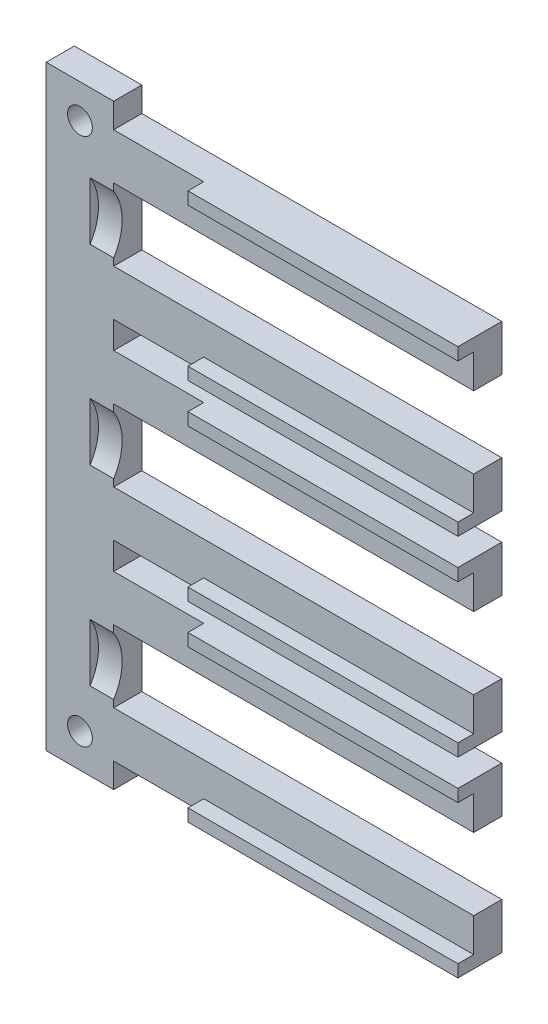
SolidWorks part; units mm, degrees
other "Spring Front Grip Acetal Guide Comb"
other "Spring Front Grip Acetal Guide Comb Left"
ref_plane "Front Plane" through (0, 0, 0) normal (0, 0, 1) x (1, 0, 0)
ref_plane "Top Plane" through (0, 0, 0) normal (0, 1, 0) x (1, 0, 0)
ref_plane "Right Plane" through (0, 0, 0) normal (1, 0, 0) x (0, 0, -1)
sketch3d "Front Grip Acetal Guide Comb sketch datum points"
  point P0 (-66.2917, -55.5, 8.5)
  point P1 (-56.2917, -55.5, 8.5)
  point P2 (-66.2917, -45.5, 8.5)
ref_plane "Front Grip Acetal Guide Comb sketch plane" through (0, 0, 8.5) normal (0, 0, 1) x (1, 0, 0)
sketch "Front Grip Acetal Guide Comb sketch" plane through (0, 0, 8.5) normal (0, 0, 1) x (1, 0, 0)
  line L0 (-66.2917, -55.5) -> (-60.2917, -55.5)
  line L1 (-60.2917, -55.5) -> (-60.2917, -2.5)
  line L2 (-60.2917, -2.5) -> (-66.2917, -2.5)
  line L3 (-66.2917, -2.5) -> (-66.2917, -55.5)
extrude "Front Grip Acetal Guide Comb" add sketch "Front Grip Acetal Guide Comb sketch" along normal blind 2.5 separate body
sketch3d "Grip Guide Ledge 1 Lower sketch datum points"
  point P0 (-60.3917, -8.8, 8.5)
  point P1 (-50.3917, -8.8, 8.5)
  point P2 (-60.3917, 1.2, 8.5)
ref_plane "Grip Guide Ledge 1 Lower sketch plane" through (0, 0, 8.5) normal (0, 0, 1) x (1, 0, 0)
sketch "Grip Guide Ledge 1 Lower sketch" plane through (0, 0, 8.5) normal (0, 0, 1) x (1, 0, 0)
  line L0 (-60.3917, -8.8) -> (-28.2917, -8.8)
  line L1 (-28.2917, -8.8) -> (-28.2917, -4.7)
  line L2 (-28.2917, -4.7) -> (-60.3917, -4.7)
  line L3 (-60.3917, -4.7) -> (-60.3917, -8.8)
extrude "Grip Guide Ledge 1 Lower" add sketch "Grip Guide Ledge 1 Lower sketch" along normal blind 2.5
sketch3d "Grip Guide Ledge 1 Upper sketch datum points"
  point P0 (-60.3917, -19.3, 8.5)
  point P1 (-50.3917, -19.3, 8.5)
  point P2 (-60.3917, -9.3, 8.5)
ref_plane "Grip Guide Ledge 1 Upper sketch plane" through (0, 0, 8.5) normal (0, 0, 1) x (1, 0, 0)
sketch "Grip Guide Ledge 1 Upper sketch" plane through (0, 0, 8.5) normal (0, 0, 1) x (1, 0, 0)
  line L0 (-60.3917, -19.3) -> (-28.2917, -19.3)
  line L1 (-28.2917, -19.3) -> (-28.2917, -15.2)
  line L2 (-28.2917, -15.2) -> (-60.3917, -15.2)
  line L3 (-60.3917, -15.2) -> (-60.3917, -19.3)
extrude "Grip Guide Ledge 1 Upper" add sketch "Grip Guide Ledge 1 Upper sketch" along normal blind 2.5
sketch3d "Grip Guide Fence 1 Lower sketch datum points"
  point P0 (-52.2917, -5.8, 10.9)
  point P1 (-42.2917, -5.8, 10.9)
  point P2 (-52.2917, 4.2, 10.9)
ref_plane "Grip Guide Fence 1 Lower sketch plane" through (0, 0, 10.9) normal (0, 0, 1) x (1, 0, 0)
sketch "Grip Guide Fence 1 Lower sketch" plane through (0, 0, 10.9) normal (0, 0, 1) x (1, 0, 0)
  line L0 (-52.2917, -5.8) -> (-28.2917, -5.8)
  line L1 (-28.2917, -5.8) -> (-28.2917, -4.7)
  line L2 (-28.2917, -4.7) -> (-52.2917, -4.7)
  line L3 (-52.2917, -4.7) -> (-52.2917, -5.8)
extrude "Grip Guide Fence 1 Lower" add sketch "Grip Guide Fence 1 Lower sketch" along normal blind 1.5
sketch3d "Grip Guide Fence 1 Upper sketch datum points"
  point P0 (-52.2917, -19.3, 10.9)
  point P1 (-42.2917, -19.3, 10.9)
  point P2 (-52.2917, -9.3, 10.9)
ref_plane "Grip Guide Fence 1 Upper sketch plane" through (0, 0, 10.9) normal (0, 0, 1) x (1, 0, 0)
sketch "Grip Guide Fence 1 Upper sketch" plane through (0, 0, 10.9) normal (0, 0, 1) x (1, 0, 0)
  line L0 (-52.2917, -19.3) -> (-28.2917, -19.3)
  line L1 (-28.2917, -19.3) -> (-28.2917, -18.2)
  line L2 (-28.2917, -18.2) -> (-52.2917, -18.2)
  line L3 (-52.2917, -18.2) -> (-52.2917, -19.3)
extrude "Grip Guide Fence 1 Upper" add sketch "Grip Guide Fence 1 Upper sketch" along normal blind 1.5
sketch3d "Grip Guide Ledge 2 Lower sketch datum points"
  point P0 (-60.3917, -25.8, 8.5)
  point P1 (-50.3917, -25.8, 8.5)
  point P2 (-60.3917, -15.8, 8.5)
ref_plane "Grip Guide Ledge 2 Lower sketch plane" through (0, 0, 8.5) normal (0, 0, 1) x (1, 0, 0)
sketch "Grip Guide Ledge 2 Lower sketch" plane through (0, 0, 8.5) normal (0, 0, 1) x (1, 0, 0)
  line L0 (-60.3917, -25.8) -> (-28.2917, -25.8)
  line L1 (-28.2917, -25.8) -> (-28.2917, -21.7)
  line L2 (-28.2917, -21.7) -> (-60.3917, -21.7)
  line L3 (-60.3917, -21.7) -> (-60.3917, -25.8)
extrude "Grip Guide Ledge 2 Lower" add sketch "Grip Guide Ledge 2 Lower sketch" along normal blind 2.5
sketch3d "Grip Guide Ledge 2 Upper sketch datum points"
  point P0 (-60.3917, -36.3, 8.5)
  point P1 (-50.3917, -36.3, 8.5)
  point P2 (-60.3917, -26.3, 8.5)
ref_plane "Grip Guide Ledge 2 Upper sketch plane" through (0, 0, 8.5) normal (0, 0, 1) x (1, 0, 0)
sketch "Grip Guide Ledge 2 Upper sketch" plane through (0, 0, 8.5) normal (0, 0, 1) x (1, 0, 0)
  line L0 (-60.3917, -36.3) -> (-28.2917, -36.3)
  line L1 (-28.2917, -36.3) -> (-28.2917, -32.2)
  line L2 (-28.2917, -32.2) -> (-60.3917, -32.2)
  line L3 (-60.3917, -32.2) -> (-60.3917, -36.3)
extrude "Grip Guide Ledge 2 Upper" add sketch "Grip Guide Ledge 2 Upper sketch" along normal blind 2.5
sketch3d "Grip Guide Fence 2 Lower sketch datum points"
  point P0 (-52.2917, -22.8, 10.9)
  point P1 (-42.2917, -22.8, 10.9)
  point P2 (-52.2917, -12.8, 10.9)
ref_plane "Grip Guide Fence 2 Lower sketch plane" through (0, 0, 10.9) normal (0, 0, 1) x (1, 0, 0)
sketch "Grip Guide Fence 2 Lower sketch" plane through (0, 0, 10.9) normal (0, 0, 1) x (1, 0, 0)
  line L0 (-52.2917, -22.8) -> (-28.2917, -22.8)
  line L1 (-28.2917, -22.8) -> (-28.2917, -21.7)
  line L2 (-28.2917, -21.7) -> (-52.2917, -21.7)
  line L3 (-52.2917, -21.7) -> (-52.2917, -22.8)
extrude "Grip Guide Fence 2 Lower" add sketch "Grip Guide Fence 2 Lower sketch" along normal blind 1.5
sketch3d "Grip Guide Fence 2 Upper sketch datum points"
  point P0 (-52.2917, -36.3, 10.9)
  point P1 (-42.2917, -36.3, 10.9)
  point P2 (-52.2917, -26.3, 10.9)
ref_plane "Grip Guide Fence 2 Upper sketch plane" through (0, 0, 10.9) normal (0, 0, 1) x (1, 0, 0)
sketch "Grip Guide Fence 2 Upper sketch" plane through (0, 0, 10.9) normal (0, 0, 1) x (1, 0, 0)
  line L0 (-52.2917, -36.3) -> (-28.2917, -36.3)
  line L1 (-28.2917, -36.3) -> (-28.2917, -35.2)
  line L2 (-28.2917, -35.2) -> (-52.2917, -35.2)
  line L3 (-52.2917, -35.2) -> (-52.2917, -36.3)
extrude "Grip Guide Fence 2 Upper" add sketch "Grip Guide Fence 2 Upper sketch" along normal blind 1.5
sketch3d "Grip Guide Ledge 3 Lower sketch datum points"
  point P0 (-60.3917, -42.8, 8.5)
  point P1 (-50.3917, -42.8, 8.5)
  point P2 (-60.3917, -32.8, 8.5)
ref_plane "Grip Guide Ledge 3 Lower sketch plane" through (0, 0, 8.5) normal (0, 0, 1) x (1, 0, 0)
sketch "Grip Guide Ledge 3 Lower sketch" plane through (0, 0, 8.5) normal (0, 0, 1) x (1, 0, 0)
  line L0 (-60.3917, -42.8) -> (-28.2917, -42.8)
  line L1 (-28.2917, -42.8) -> (-28.2917, -38.7)
  line L2 (-28.2917, -38.7) -> (-60.3917, -38.7)
  line L3 (-60.3917, -38.7) -> (-60.3917, -42.8)
extrude "Grip Guide Ledge 3 Lower" add sketch "Grip Guide Ledge 3 Lower sketch" along normal blind 2.5
sketch3d "Grip Guide Ledge 3 Upper sketch datum points"
  point P0 (-60.3917, -53.3, 8.5)
  point P1 (-50.3917, -53.3, 8.5)
  point P2 (-60.3917, -43.3, 8.5)
ref_plane "Grip Guide Ledge 3 Upper sketch plane" through (0, 0, 8.5) normal (0, 0, 1) x (1, 0, 0)
sketch "Grip Guide Ledge 3 Upper sketch" plane through (0, 0, 8.5) normal (0, 0, 1) x (1, 0, 0)
  line L0 (-60.3917, -53.3) -> (-28.2917, -53.3)
  line L1 (-28.2917, -53.3) -> (-28.2917, -49.2)
  line L2 (-28.2917, -49.2) -> (-60.3917, -49.2)
  line L3 (-60.3917, -49.2) -> (-60.3917, -53.3)
extrude "Grip Guide Ledge 3 Upper" add sketch "Grip Guide Ledge 3 Upper sketch" along normal blind 2.5
sketch3d "Grip Guide Fence 3 Lower sketch datum points"
  point P0 (-52.2917, -39.8, 10.9)
  point P1 (-42.2917, -39.8, 10.9)
  point P2 (-52.2917, -29.8, 10.9)
ref_plane "Grip Guide Fence 3 Lower sketch plane" through (0, 0, 10.9) normal (0, 0, 1) x (1, 0, 0)
sketch "Grip Guide Fence 3 Lower sketch" plane through (0, 0, 10.9) normal (0, 0, 1) x (1, 0, 0)
  line L0 (-52.2917, -39.8) -> (-28.2917, -39.8)
  line L1 (-28.2917, -39.8) -> (-28.2917, -38.7)
  line L2 (-28.2917, -38.7) -> (-52.2917, -38.7)
  line L3 (-52.2917, -38.7) -> (-52.2917, -39.8)
extrude "Grip Guide Fence 3 Lower" add sketch "Grip Guide Fence 3 Lower sketch" along normal blind 1.5
sketch3d "Grip Guide Fence 3 Upper sketch datum points"
  point P0 (-52.2917, -53.3, 10.9)
  point P1 (-42.2917, -53.3, 10.9)
  point P2 (-52.2917, -43.3, 10.9)
ref_plane "Grip Guide Fence 3 Upper sketch plane" through (0, 0, 10.9) normal (0, 0, 1) x (1, 0, 0)
sketch "Grip Guide Fence 3 Upper sketch" plane through (0, 0, 10.9) normal (0, 0, 1) x (1, 0, 0)
  line L0 (-52.2917, -53.3) -> (-28.2917, -53.3)
  line L1 (-28.2917, -53.3) -> (-28.2917, -52.2)
  line L2 (-28.2917, -52.2) -> (-52.2917, -52.2)
  line L3 (-52.2917, -52.2) -> (-52.2917, -53.3)
extrude "Grip Guide Fence 3 Upper" add sketch "Grip Guide Fence 3 Upper sketch" along normal blind 1.5
sketch3d "Front Guide Screw Clearance 1 sketch datum points"
  point P0 (-63.2917, -5.5, 8.4)
  point P1 (-53.2917, -5.5, 8.4)
  point P2 (-63.2917, 4.5, 8.4)
ref_plane "Front Guide Screw Clearance 1 sketch plane" through (0, 0, 8.4) normal (0, 0, 1) x (1, 0, 0)
sketch "Front Guide Screw Clearance 1 sketch" plane through (0, 0, 8.4) normal (0, 0, 1) x (1, 0, 0)
  circle A0 centre (-63.2917, -5.5) radius 1.1
extrude "Front Guide Screw Clearance 1" cut sketch "Front Guide Screw Clearance 1 sketch" along normal blind 2.7
sketch3d "Front Guide Screw Clearance 2 sketch datum points"
  point P0 (-63.2917, -52.5, 8.4)
  point P1 (-53.2917, -52.5, 8.4)
  point P2 (-63.2917, -42.5, 8.4)
ref_plane "Front Guide Screw Clearance 2 sketch plane" through (0, 0, 8.4) normal (0, 0, 1) x (1, 0, 0)
sketch "Front Guide Screw Clearance 2 sketch" plane through (0, 0, 8.4) normal (0, 0, 1) x (1, 0, 0)
  circle A0 centre (-63.2917, -52.5) radius 1.1
extrude "Front Guide Screw Clearance 2" cut sketch "Front Guide Screw Clearance 2 sketch" along normal blind 2.7
sketch3d "Outlet seat clearance 1 sketch datum points"
  point P0 (-62.3917, -12, 15)
  point P1 (-62.3917, -2, 15)
  point P2 (-62.3917, -12, 25)
ref_plane "Outlet seat clearance 1 sketch plane" through (-62.3917, 0, 0) normal (1, 0, 0) x (0, 0, -1)
sketch "Outlet seat clearance 1 sketch" plane through (-62.3917, 0, 0) normal (1, 0, 0) x (0, 0, -1)
  circle A0 centre (-15, -12) radius 4.75
extrude "Outlet seat clearance 1" cut sketch "Outlet seat clearance 1 sketch" along normal blind 2.2
sketch3d "Outlet seat clearance 2 sketch datum points"
  point P0 (-62.3917, -29, 15)
  point P1 (-62.3917, -19, 15)
  point P2 (-62.3917, -29, 25)
ref_plane "Outlet seat clearance 2 sketch plane" through (-62.3917, 0, 0) normal (1, 0, 0) x (0, 0, -1)
sketch "Outlet seat clearance 2 sketch" plane through (-62.3917, 0, 0) normal (1, 0, 0) x (0, 0, -1)
  circle A0 centre (-15, -29) radius 4.75
extrude "Outlet seat clearance 2" cut sketch "Outlet seat clearance 2 sketch" along normal blind 2.2
sketch3d "Outlet seat clearance 3 sketch datum points"
  point P0 (-62.3917, -46, 15)
  point P1 (-62.3917, -36, 15)
  point P2 (-62.3917, -46, 25)
ref_plane "Outlet seat clearance 3 sketch plane" through (-62.3917, 0, 0) normal (1, 0, 0) x (0, 0, -1)
sketch "Outlet seat clearance 3 sketch" plane through (-62.3917, 0, 0) normal (1, 0, 0) x (0, 0, -1)
  circle A0 centre (-15, -46) radius 4.75
extrude "Outlet seat clearance 3" cut sketch "Outlet seat clearance 3 sketch" along normal blind 2.2
sketch3d "Mirror1 profile datum points"
  point P0 (0, 0, 0)
  point P1 (10, 0, 0)
  point P2 (0, 0, 10)
ref_plane "Mirror1 profile plane" through (0, 0, 0) normal (0, -1, 0) x (-1, 0, 0)
mirror "Mirror1" about plane through (0, 0, 0) normal (0, -1, 0) of bodies 118
delete or keep bodies "Remove1" type delete bodies bodies 118
